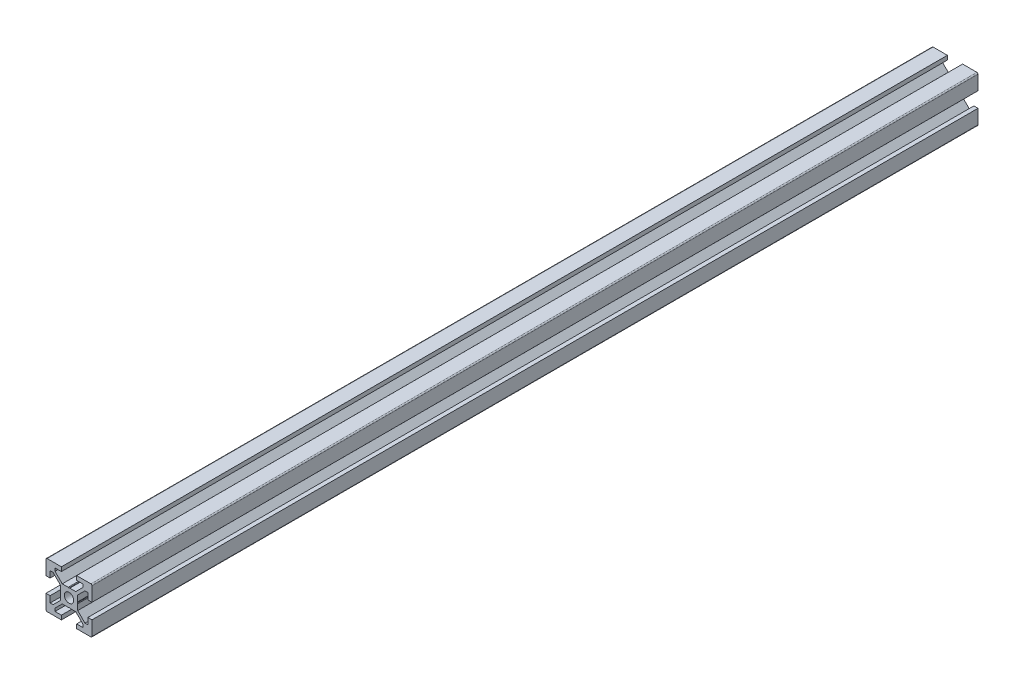
SolidWorks part; units mm, degrees
ref_plane "Front Plane" through (0, 0, 0) normal (0, 0, 1) x (1, 0, 0)
ref_plane "Top Plane" through (0, 0, 0) normal (0, 1, 0) x (1, 0, 0)
ref_plane "Right Plane" through (0, 0, 0) normal (1, 0, 0) x (0, 0, -1)
sketch "Sketch1" plane through (0, 0, 0) normal (0, 0, 1) x (1, 0, 0)
  line L0 (-3.3, 10) -> (-3.3, 8.2)
  line L1 (0, 0) -> (50000, 0) construction
  line L2 (-10, 3.3) -> (-10, 10)
  line L3 (-10, 10) -> (-3.3, 10)
  line L4 (0, 0) -> (0, 50000) construction
  line L5 (-10, -10) -> (10, 10) construction
  line L6 (-10, 10) -> (10, -10) construction
  line L7 (-2.9315, -3.78) -> (-0.34, -3.78)
  line L8 (-3.78, -2.9315) -> (-3.78, -0.34)
  line L9 (-2.9315, 3.78) -> (-0.34, 3.78)
  line L10 (3.78, -2.9315) -> (3.78, -0.34)
  line L11 (-3.78, -3.78) -> (3.78, 3.78) construction
  line L12 (-3.78, 3.78) -> (3.78, -3.78) construction
  line L13 (-6.08, 8.2) -> (-3.3, 8.2)
  line L14 (-8.2, 6.08) -> (-8.2, 3.3)
  line L15 (-8.2, 3.3) -> (-10, 3.3)
  line L16 (-8.2, 6.08) -> (-6.9285, 6.08)
  line L17 (-6.08, 8.2) -> (-6.08, 6.9285)
  line L18 (-6.9285, 6.08) -> (-3.78, 2.9315)
  line L19 (-6.08, 6.9285) -> (-2.9315, 3.78)
  line L20 (8.2, 6.08) -> (6.9285, 6.08)
  line L21 (8.2, 6.08) -> (8.2, 3.3)
  line L22 (8.2, 3.3) -> (10, 3.3)
  line L23 (10, 3.3) -> (10, 10)
  line L24 (10, 10) -> (3.3, 10)
  line L25 (3.3, 10) -> (3.3, 8.2)
  line L26 (6.08, 8.2) -> (3.3, 8.2)
  line L27 (6.08, 8.2) -> (6.08, 6.9285)
  line L28 (6.08, 6.9285) -> (2.9315, 3.78)
  line L29 (6.9285, 6.08) -> (3.78, 2.9315)
  line L30 (6.9285, -6.08) -> (3.78, -2.9315)
  line L31 (6.08, -6.9285) -> (2.9315, -3.78)
  line L32 (6.08, -8.2) -> (6.08, -6.9285)
  line L33 (6.08, -8.2) -> (3.3, -8.2)
  line L34 (3.3, -10) -> (3.3, -8.2)
  line L35 (10, -10) -> (3.3, -10)
  line L36 (10, -3.3) -> (10, -10)
  line L37 (8.2, -3.3) -> (10, -3.3)
  line L38 (8.2, -6.08) -> (8.2, -3.3)
  line L39 (8.2, -6.08) -> (6.9285, -6.08)
  line L40 (-6.08, -6.9285) -> (-2.9315, -3.78)
  line L41 (-6.9285, -6.08) -> (-3.78, -2.9315)
  line L42 (-6.08, -8.2) -> (-6.08, -6.9285)
  line L43 (-8.2, -6.08) -> (-6.9285, -6.08)
  line L44 (-8.2, -3.3) -> (-10, -3.3)
  line L45 (-8.2, -6.08) -> (-8.2, -3.3)
  line L46 (-6.08, -8.2) -> (-3.3, -8.2)
  line L47 (-10, -10) -> (-3.3, -10)
  line L48 (-10, -3.3) -> (-10, -10)
  line L49 (-3.3, -10) -> (-3.3, -8.2)
  line L50 (-0.34, 3.78) -> (0, 3.66)
  line L51 (0.34, 3.78) -> (0, 3.66)
  line L52 (0.34, 3.78) -> (2.9315, 3.78)
  line L53 (-3.78, -0.34) -> (-3.66, 0)
  line L54 (-3.78, 0.34) -> (-3.66, 0)
  line L55 (3.78, 0.34) -> (3.66, 0)
  line L56 (3.78, -0.34) -> (3.66, 0)
  line L57 (-0.34, -3.78) -> (0, -3.66)
  line L58 (0.34, -3.78) -> (0, -3.66)
  line L59 (3.78, 0.34) -> (3.78, 2.9315)
  line L60 (0.34, -3.78) -> (2.9315, -3.78)
  line L61 (-3.78, 0.34) -> (-3.78, 2.9315)
  circle A0 centre (0, 0) radius 2.05
  point P0 (0, 0)
  dimension "D3" = 4.1
  dimension "D1" = 20
  dimension "D2" = 20
  dimension "D4" = 7.56
  dimension "D5" = 6.7
  dimension "D6" = 6.7
  dimension "D7" = 0.6
  dimension "D8" = 3.92
  dimension "D9" = 0.34
  dimension "D10" = 0.12
extrude "Boss-Extrude1" add sketch "Sketch1" along normal blind 385
fillet "Fillet1" radius 0.5 4 edges at (-10, 10, 192.5) (-10, -10, 192.5) (10, -10, 192.5) (10, 10, 192.5)
